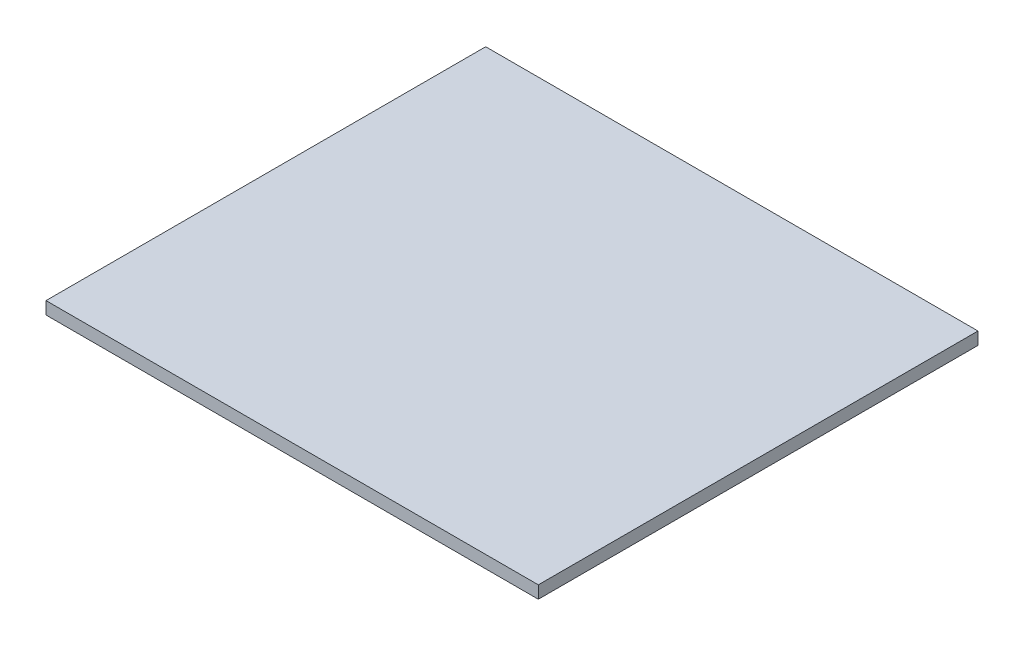
SolidWorks part; units mm, degrees
ref_plane "Front" through (0, 0, 0) normal (0, 0, 1) x (1, 0, 0)
ref_plane "Top" through (0, 0, 0) normal (0, 1, 0) x (1, 0, 0)
ref_plane "Right" through (0, 0, 0) normal (1, 0, 0) x (0, 0, -1)
sketch "Sketch1" plane through (0, 0, 0) normal (0, 1, 0) x (1, 0, 0)
  line L1 (0, 0) -> (375, 0)
  line L2 (0, 0) -> (0, 334.9)
  line L3 (0, 334.9) -> (375, 334.9)
  line L4 (375, 0) -> (375, 334.9)
  dimension "D1" = 375
  dimension "D2" = 334.9
extrude "Boss-Extrude1" add sketch "Sketch1" along normal blind 9.525
